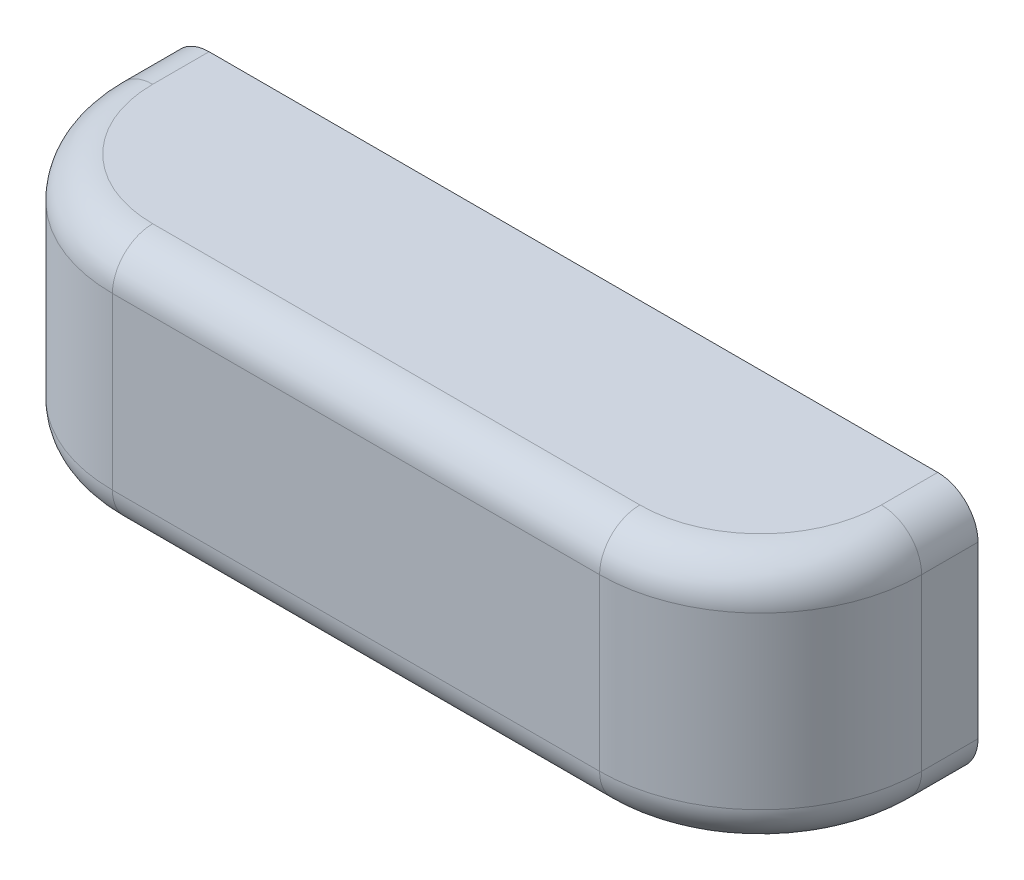
SolidWorks part; units mm, degrees
material "Custom Plastic"
ref_plane "X-Y Datum" through (0, 0, 0) normal (0, 0, 1) x (1, 0, 0)
ref_plane "X-Z Datum" through (0, 0, 0) normal (0, 1, 0) x (1, 0, 0)
ref_plane "Y-Z Datum" through (0, 0, 0) normal (1, 0, 0) x (0, 0, -1)
sketch "Sketch1" plane through (0, 0, 0) normal (0, 0, 1) x (1, 0, 0)
  line L1 (-50.25, 15.575) -> (50.25, 15.575)
  line L2 (-50.25, 15.575) -> (-50.25, -15.575)
  line L3 (-50.25, -15.575) -> (50.25, -15.575)
  line L4 (50.25, 15.575) -> (50.25, -15.575)
  line L5 (-50.25, 15.575) -> (50.25, -15.575) construction
  line L6 (-50.25, -15.575) -> (50.25, 15.575) construction
  point P0 (0, 0)
  dimension "D1" = 100.5
  dimension "D2" = 31.15
extrude "Boss-Extrude1" add sketch "Sketch1" along normal blind 27
fillet "Fillet1" radius 20 2 edges at (50.25, 0, 27) (-50.25, 0, 27)
fillet "Fillet2" radius 5 10 edges at (50.25, 15.575, 3.5) (44.3921, 15.575, 21.1421) (-50.25, 15.575, 3.5) (-44.3921, 15.575, 21.1421) (-50.25, -15.575, 3.5) (-44.3921, -15.575, 21.1421) (50.25, -15.575, 3.5) (44.3921, -15.575, 21.1421) (0, 15.575, 27) (0, -15.575, 27)
